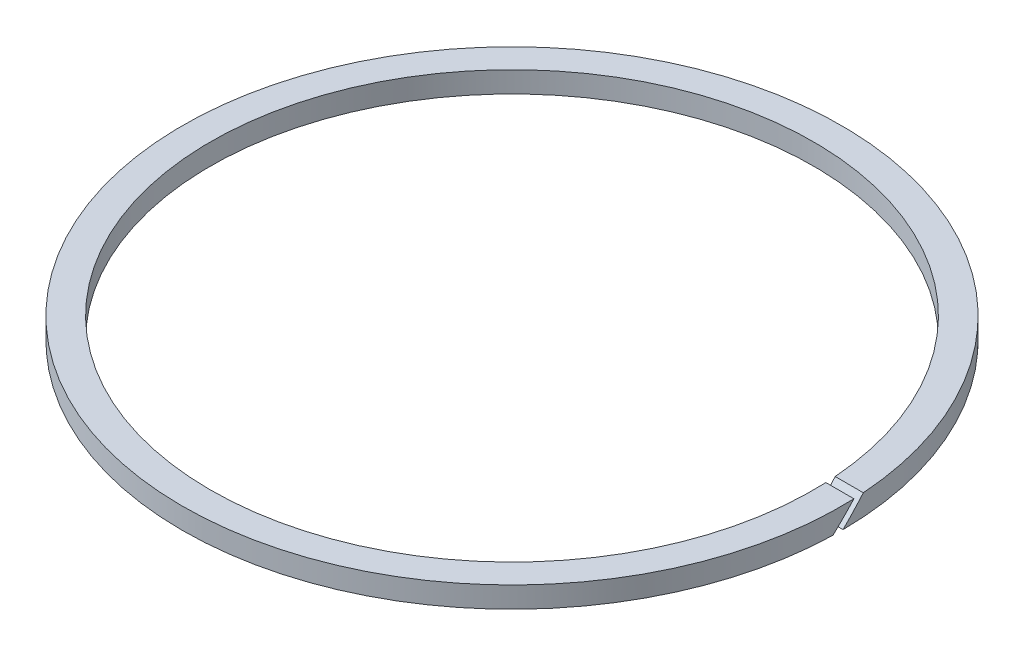
SolidWorks part; units mm, degrees
ref_plane "Front Plane" through (0, 0, 0) normal (0, 0, 1) x (1, 0, 0)
ref_plane "Top Plane" through (0, 0, 0) normal (0, 1, 0) x (1, 0, 0)
ref_plane "Right Plane" through (0, 0, 0) normal (1, 0, 0) x (0, 0, -1)
sketch "Sketch1" plane through (0, 0, 0) normal (0, 1, 0) x (1, 0, 0)
  circle A0 centre (0, 0) radius 47
  circle A1 centre (0, 0) radius 43
  dimension "D1" = 94
  dimension "D2" = 86
extrude "Boss-Extrude1" add sketch "Sketch1" along normal mid plane 3
sketch "Sketch2" plane through (0, 0, 0) normal (1, 0, 0) x (0, 0, -1)
  line L0 (0, 0) -> (-47, 0) construction
  line L1 (-47, 1.5) -> (-47, -1.5) construction
  line L2 (4.8532, 3.8532) -> (-2.8532, -3.8532) construction
  line L3 (4.4997, 4.2068) -> (-3.2068, -3.4997)
  line L4 (5.2068, 3.4997) -> (-2.4997, -4.2068)
  line L5 (5.2068, 3.4997) -> (4.4997, 4.2068)
  line L6 (-2.4997, -4.2068) -> (-3.2068, -3.4997)
  point P8 (1, 0)
  dimension "D1" = 135
  dimension "D4" = 1
  dimension "D2" = 0.5
  dimension "D3" = 0.5
extrude "Cut-Extrude1" cut sketch "Sketch2" along normal through all
